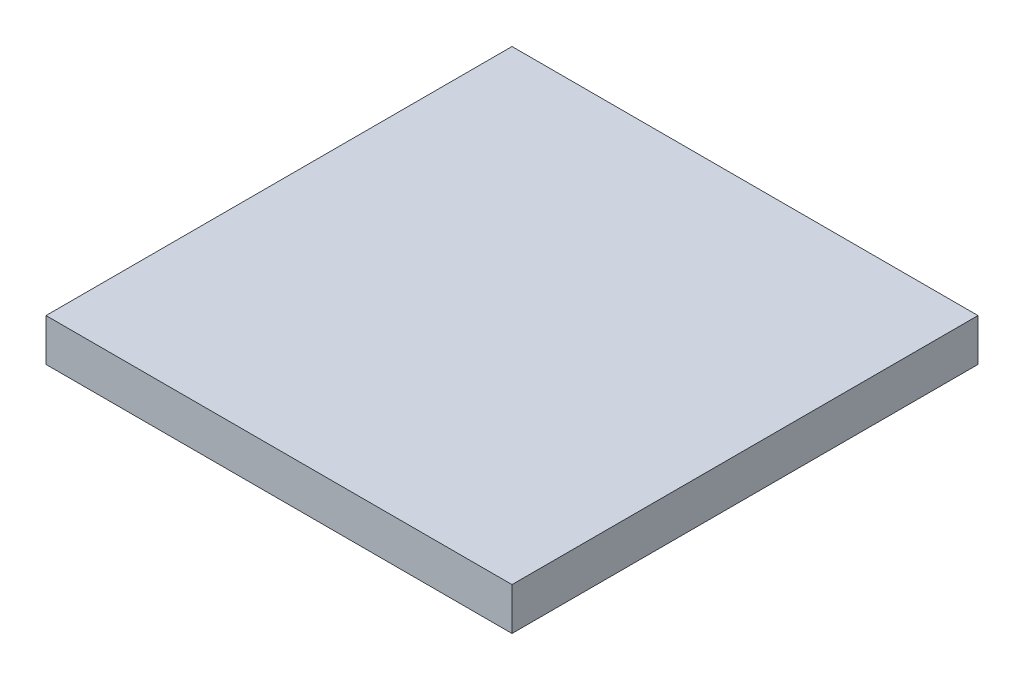
SolidWorks part; units mm, degrees
material "Pino"
ref_plane "Alzado" through (0, 0, 0) normal (0, 0, 1) x (1, 0, 0)
ref_plane "Planta" through (0, 0, 0) normal (0, 1, 0) x (1, 0, 0)
ref_plane "Vista lateral" through (0, 0, 0) normal (1, 0, 0) x (0, 0, -1)
sketch "Croquis1" plane through (0, 0, 0) normal (0, 1, 0) x (1, 0, 0)
  line L0 (0, 0) -> (0, 55)
  line L1 (0, 55) -> (55, 55)
  line L2 (55, 55) -> (55, 0)
  line L3 (55, 0) -> (0, 0)
  dimension "D1" = 55
extrude "Saliente-Extruir1" add sketch "Croquis1" along normal blind 5
